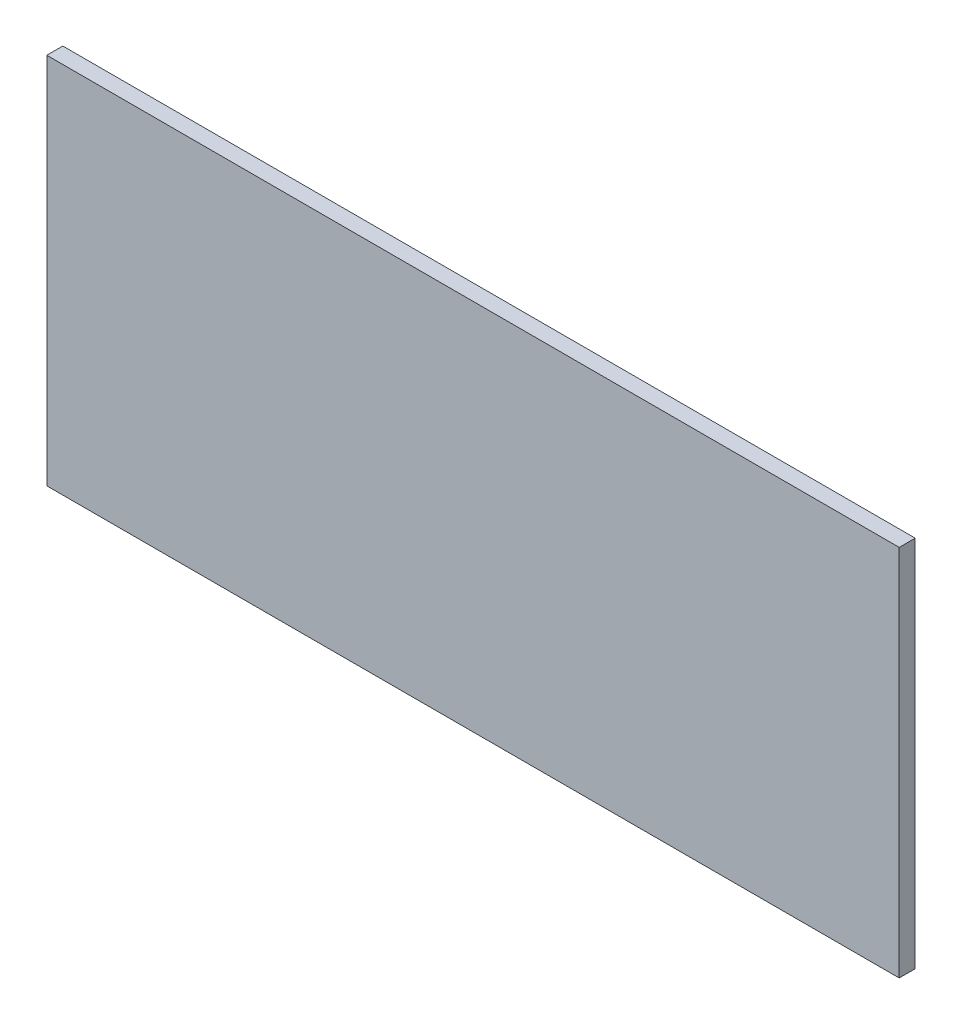
SolidWorks part; units mm, degrees
ref_plane "Front" through (0, 0, 0) normal (0, 0, 1) x (1, 0, 0)
ref_plane "Top" through (0, 0, 0) normal (0, 1, 0) x (1, 0, 0)
ref_plane "Right" through (0, 0, 0) normal (1, 0, 0) x (0, 0, -1)
sketch "Sketch1" plane through (0, 0, 0) normal (0, 0, 1) x (1, 0, 0)
  line L0 (0, 0) -> (0, 70)
  line L1 (0, 70) -> (-160, 70)
  line L2 (-160, 70) -> (-160, 0)
  line L3 (-160, 0) -> (0, 0)
  dimension "D1" = 70
  dimension "D2" = 160
extrude "Boss-Extrude1" add sketch "Sketch1" along normal blind 3
